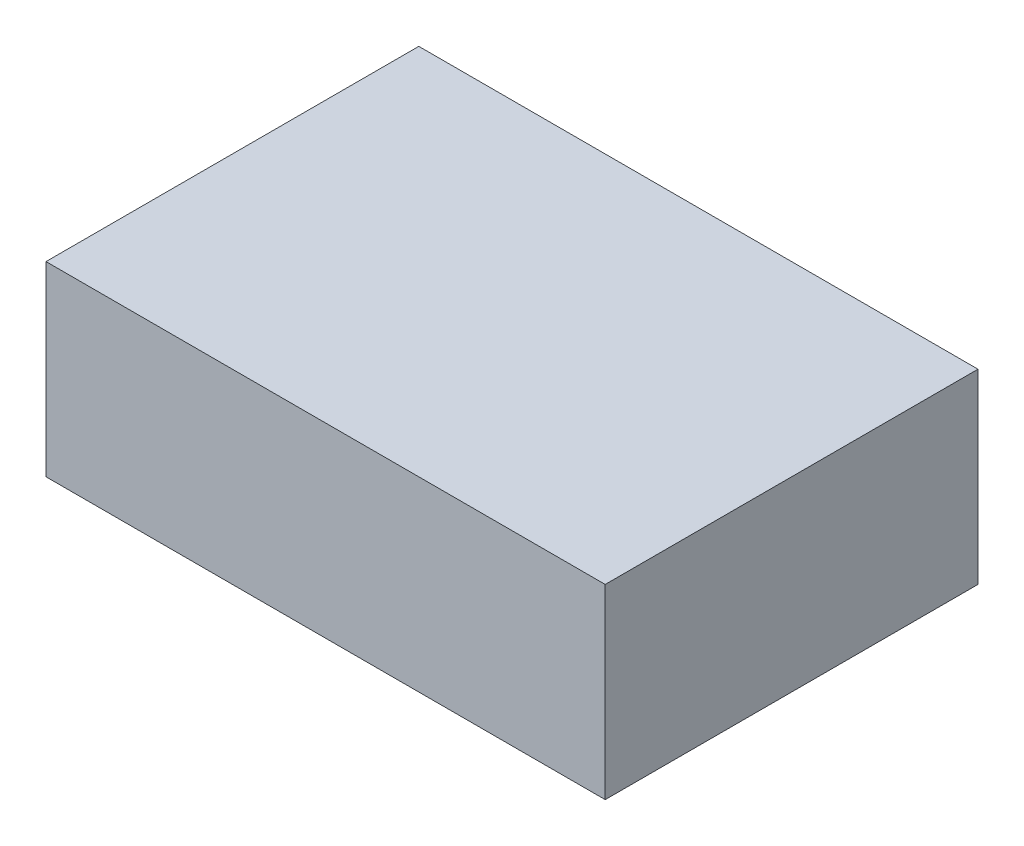
SolidWorks part; units mm, degrees
ref_plane "Спереди" through (0, 0, 0) normal (0, 0, 1) x (1, 0, 0)
ref_plane "Сверху" through (0, 0, 0) normal (0, 1, 0) x (1, 0, 0)
ref_plane "Справа" through (0, 0, 0) normal (1, 0, 0) x (0, 0, -1)
sketch "Эскиз1" plane through (0, 0, 0) normal (0, 1, 0) x (1, 0, 0)
  line L1 (-30, -20) -> (30, -20)
  line L2 (-30, -20) -> (-30, 20)
  line L3 (-30, 20) -> (30, 20)
  line L4 (30, -20) -> (30, 20)
  line L5 (-30, -20) -> (30, 20) construction
  line L6 (-30, 20) -> (30, -20) construction
  point P0 (0, 0)
  dimension "D1" = 60
  dimension "D2" = 40
extrude "Бобышка-Вытянуть1" add sketch "Эскиз1" along normal blind 20
